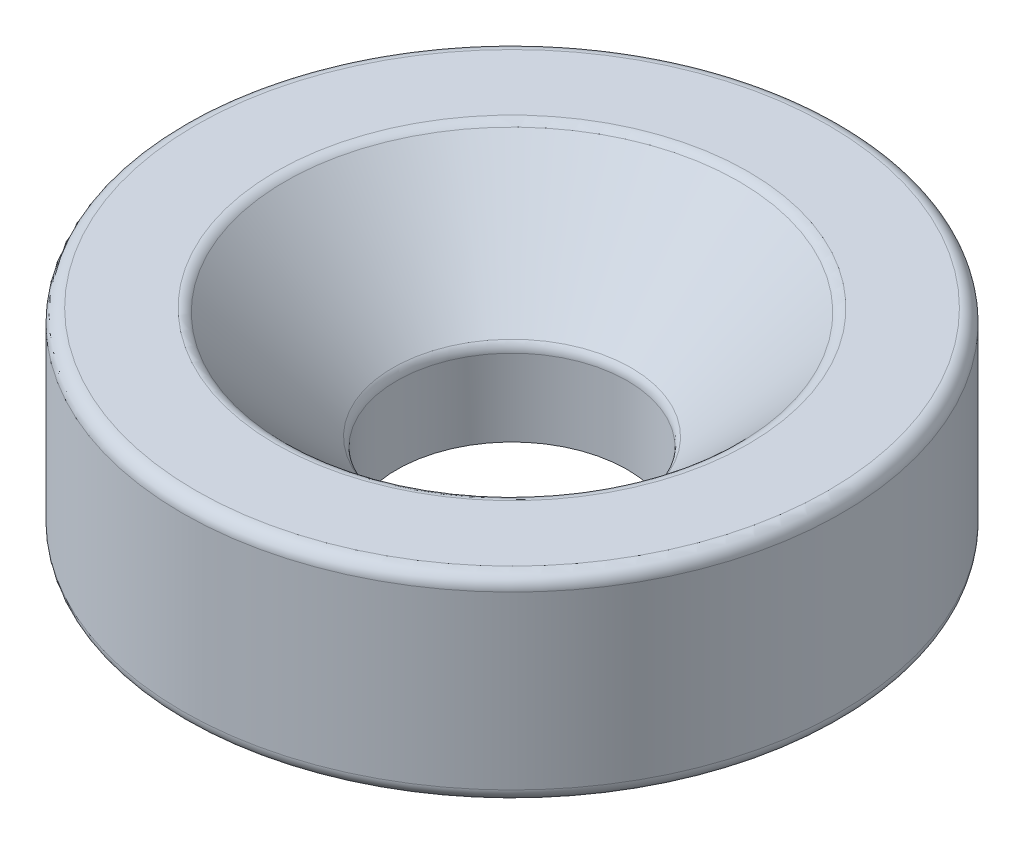
SolidWorks part; units mm, degrees
ref_plane "Front" through (0, 0, 0) normal (0, 0, 1) x (1, 0, 0)
ref_plane "Top" through (0, 0, 0) normal (0, 1, 0) x (1, 0, 0)
ref_plane "Right" through (0, 0, 0) normal (1, 0, 0) x (0, 0, -1)
sketch "Эскиз1" plane through (0, 0, 0) normal (0, 1, 0) x (1, 0, 0)
  circle A0 centre (0, 0) radius 5
  circle A1 centre (0, 0) radius 1.75
  dimension "D1" = 10
  dimension "D2" = 3.5
extrude "Бобышка-Вытянуть1" add sketch "Эскиз1" along normal blind 3
chamfer "Фаска1" distance 1.75 1 edges at (0, 3, 1.75)
fillet "Скругление1" radius 0.2 4 edges at (0, 0, 5) (0, 3, 5) (0, 3, 3.5) (0, 1.25, 1.75)
